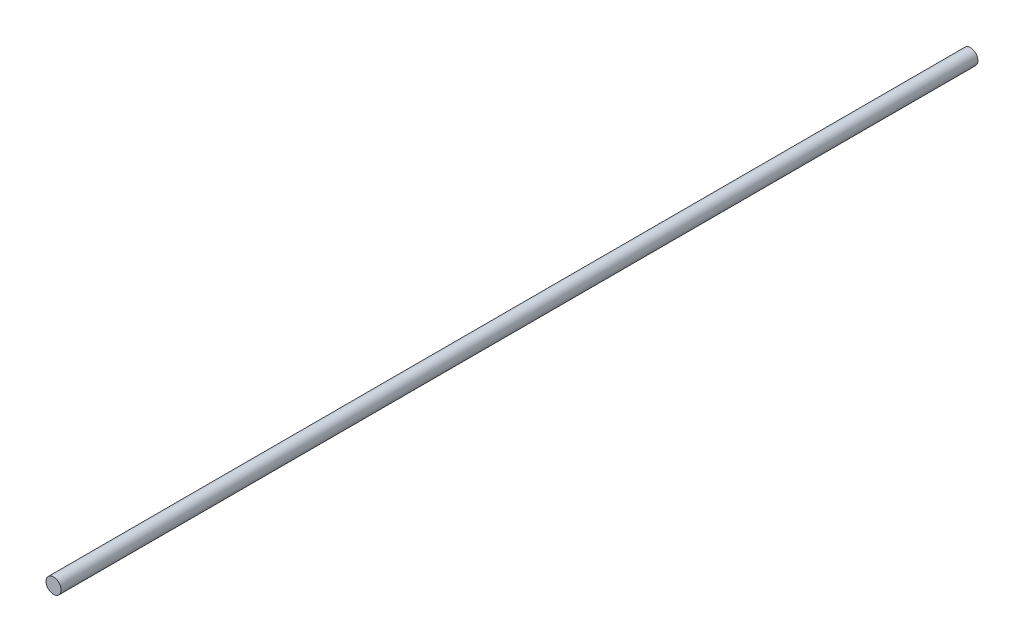
SolidWorks part; units mm, degrees
ref_plane "Front Plane" through (0, 0, 0) normal (0, 0, 1) x (1, 0, 0)
ref_plane "Top Plane" through (0, 0, 0) normal (0, 1, 0) x (1, 0, 0)
ref_plane "Right Plane" through (0, 0, 0) normal (1, 0, 0) x (0, 0, -1)
sketch "Sketch1" plane through (0, 0, 0) normal (0, 0, 1) x (1, 0, 0)
  circle A0 centre (0, 0) radius 76.2
  dimension "D1" = 152.4
extrude "Boss-Extrude1" add sketch "Sketch1" along normal up to surface (9250.6045 mm away)
